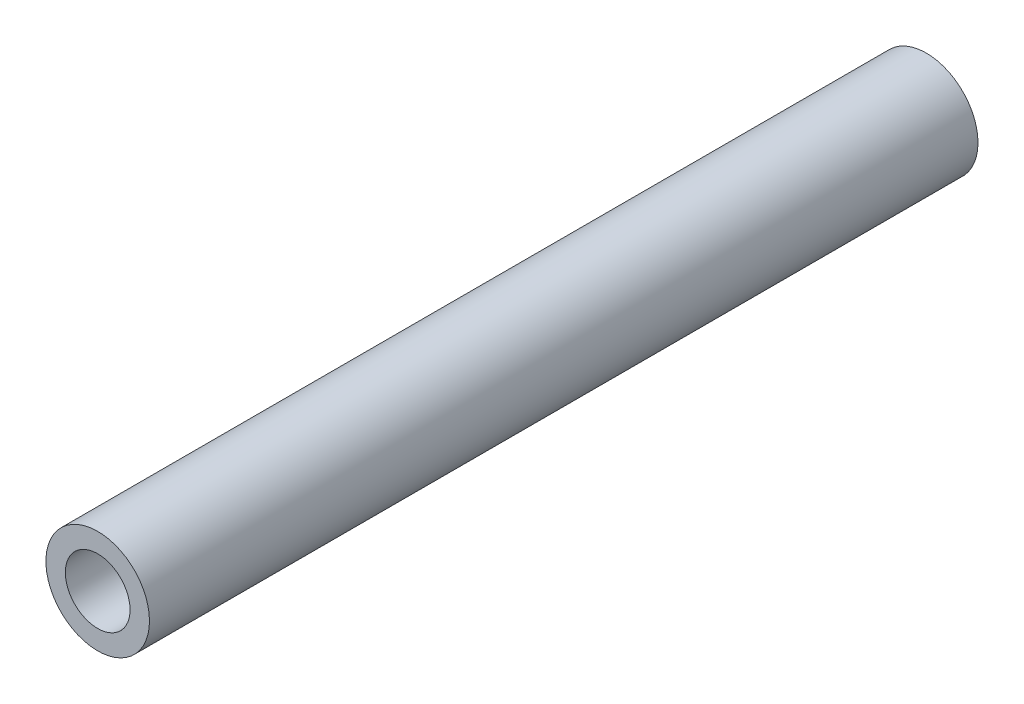
SolidWorks part; units mm, degrees
ref_plane "前视基准面" through (0, 0, 0) normal (0, 0, 1) x (1, 0, 0)
ref_plane "上视基准面" through (0, 0, 0) normal (0, 1, 0) x (1, 0, 0)
ref_plane "右视基准面" through (0, 0, 0) normal (1, 0, 0) x (0, 0, -1)
other "Configuration Table"
sketch "草图1" plane through (0, 0, 0) normal (0, 0, 1) x (1, 0, 0)
  circle A0 centre (0, 0) radius 1.25
  circle A1 centre (0, 0) radius 2
  dimension "D1" = 2.5
  dimension "D2" = 4
extrude "凸台-拉伸1" add sketch "草图1" along normal blind 32
